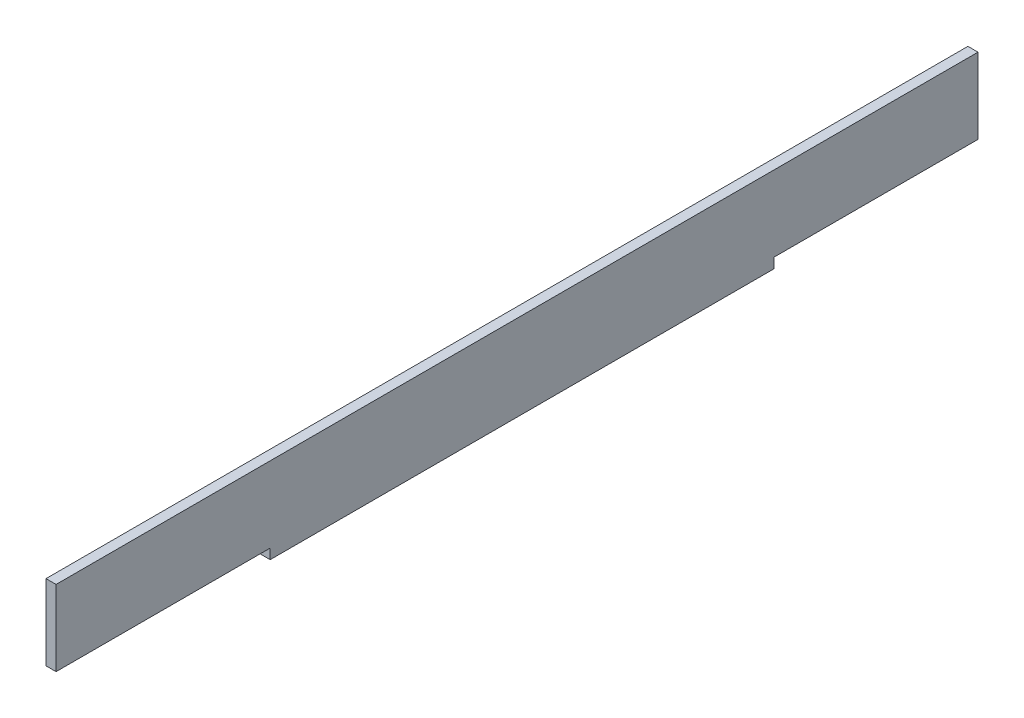
SolidWorks part; units mm, degrees
ref_plane "Front Plane" through (0, 0, 0) normal (0, 0, 1) x (1, 0, 0)
ref_plane "Top Plane" through (0, 0, 0) normal (0, 1, 0) x (1, 0, 0)
ref_plane "Right Plane" through (0, 0, 0) normal (1, 0, 0) x (0, 0, -1)
sketch "Sketch1" plane through (0, 0, 0) normal (1, 0, 0) x (0, 0, -1)
  line L0 (-117.9673, -11.4636) -> (82.0327, -11.4636)
  line L1 (82.0327, -11.4636) -> (82.0327, -7.4636)
  line L2 (82.0327, -7.4636) -> (163.0327, -7.4636)
  line L3 (163.0327, -7.4636) -> (163.0327, 22.5364)
  line L4 (163.0327, 22.5364) -> (82.0327, 22.5364)
  line L5 (82.0327, 22.5364) -> (-117.9673, 22.5364)
  line L6 (-117.9673, 22.5364) -> (-202.9673, 22.5364)
  line L7 (-202.9673, 22.5364) -> (-202.9673, -7.4636)
  line L8 (-202.9673, -7.4636) -> (-117.9673, -7.4636)
  line L9 (-117.9673, -7.4636) -> (-117.9673, -11.4636)
  dimension "D1" = 200
  dimension "D2" = 4
  dimension "D3" = 81
  dimension "D4" = 30
  dimension "D5" = 200
  dimension "D6" = 85
  dimension "D7" = 30
  dimension "D8" = 85
  dimension "D9" = 4
extrude "Boss-Extrude1" add sketch "Sketch1" along normal blind 4
